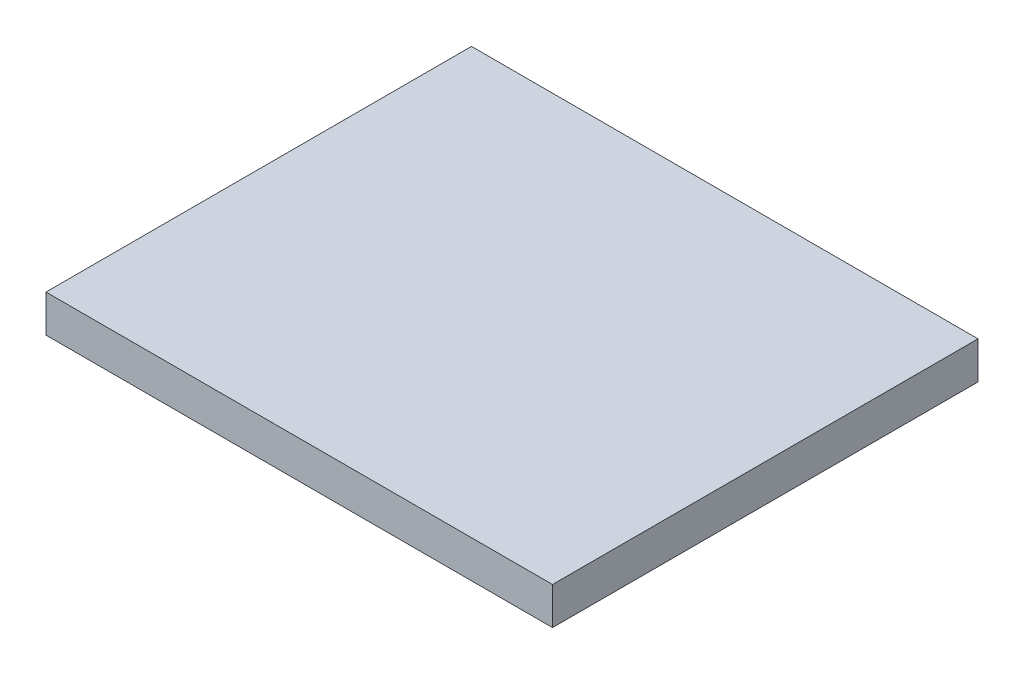
SolidWorks part; units mm, degrees
ref_plane "Front" through (0, 0, 0) normal (0, 0, 1) x (1, 0, 0)
ref_plane "Top" through (0, 0, 0) normal (0, 1, 0) x (1, 0, 0)
ref_plane "Right" through (0, 0, 0) normal (1, 0, 0) x (0, 0, -1)
sketch "Sketch1" plane through (0, 0, 0) normal (0, 1, 0) x (1, 0, 0)
  line L1 (-62.5, -52.5) -> (62.5, -52.5)
  line L2 (-62.5, -52.5) -> (-62.5, 52.5)
  line L3 (-62.5, 52.5) -> (62.5, 52.5)
  line L4 (62.5, -52.5) -> (62.5, 52.5)
  line L5 (-62.5, -52.5) -> (62.5, 52.5) construction
  line L6 (-62.5, 52.5) -> (62.5, -52.5) construction
  point P0 (0, 0)
  dimension "D1" = 125
  dimension "D2" = 105
extrude "Test_Base_Postion" add sketch "Sketch1" along normal blind 9.215
sketch "Thumb_Position" plane through (0, 9.215, 0) normal (0, 1, 0) x (1, 0, 0)
  line L0 (62.5, -52.5) -> (62.5, 52.5) construction
  line L1 (49, -12) -> (17, -12)
  line L2 (49, -12) -> (49, 43)
  line L3 (49, 43) -> (17, 43)
  line L4 (17, -12) -> (17, 43)
  line L5 (33, 43) -> (33, -12) construction
  line L6 (51, -12) -> (15, -12)
  line L7 (51, -12) -> (51, 12)
  line L8 (51, 12) -> (15, 12)
  line L9 (15, -12) -> (15, 12)
  line L10 (33, 12) -> (33, -12) construction
  line L12 (51, 0) -> (15, 0) construction
  circle A1 centre (42, 0) radius 9
  circle A2 centre (42, 0) radius 17.75 construction
  dimension "D6" = 18
  dimension "D7" = 20.5
  dimension "D5" = 35.5
  dimension "D1" = 55
  dimension "D2" = 32
  dimension "D3" = 36
  dimension "D4" = 24
sketch "Finger_Gears_Position" plane through (0, 0, 0) normal (0, -1, 0) x (1, 0, 0)
  line L0 (-30, 32) -> (-30, 49.5) construction
  line L1 (-30, 32) -> (-47.5, 32) construction
  line L2 (-30, -32) -> (-30, -49.5) construction
  line L3 (-30, -32) -> (-47.5, -32) construction
  line L4 (-62.5, -52.5) -> (-62.5, 52.5) construction
  line L5 (-62.5, 52.5) -> (62.5, 52.5) construction
  line L8 (62.5, -52.5) -> (-62.5, -52.5) construction
  line L9 (-62.5, 0) -> (62.5, 0) construction
  line L10 (62.5, 52.5) -> (62.5, -52.5) construction
  line L13 (-30, -32) -> (-43, -32) construction
  line L15 (-43, -48) -> (12, -48) construction
  line L16 (-43, -48) -> (-43, -16) construction
  line L17 (-43, -16) -> (12, -16) construction
  line L18 (12, -48) -> (12, -16) construction
  line L20 (-30, 32) -> (-43, 32) construction
  line L21 (12, -32) -> (-23, -32) construction
  line L22 (-43, 16) -> (12, 16) construction
  line L23 (-43, 16) -> (-43, 48) construction
  line L24 (-43, 48) -> (12, 48) construction
  line L25 (12, 16) -> (12, 48) construction
  line L26 (12, 32) -> (-23, 32) construction
  line L27 (-23, -32) -> (-23, 32) construction
  circle A0 centre (-30, 32) radius 17.5 construction
  circle A1 centre (-30, -32) radius 17.5 construction
  dimension "D1" = 35
  dimension "D2" = 15
  dimension "D3" = 3
  dimension "D4" = 3
  dimension "D5" = 13
  dimension "D6" = 55
  dimension "D7" = 32
  dimension "D8" = 13
  dimension "D9" = 55
  dimension "D10" = 32
  dimension "D11" = 35
  dimension "D12" = 35
sketch "Fingers_Position" plane through (0, 9.215, 0) normal (0, 1, 0) x (1, 0, 0)
  line L0 (12, 32) -> (-23, 32) construction
  line L1 (12, 16) -> (-43, 16)
  line L2 (12, 16) -> (12, 48)
  line L3 (12, 48) -> (-43, 48)
  line L4 (-43, 16) -> (-43, 48)
  line L5 (12, -48) -> (-43, -48)
  line L6 (12, -48) -> (12, -16)
  line L7 (12, -16) -> (-43, -16)
  line L8 (-43, -48) -> (-43, -16)
  line L9 (-23, 32) -> (-23, -32) construction
  line L10 (-23, -32) -> (12, -32) construction
sketch "Thumb_Knuckle_Mount_Position" plane through (0, 0, 0) normal (0, -1, 0) x (1, 0, 0)
  circle A0 centre (42, 0) radius 17.75
  dimension "D1" = 35.5
sketch "Gears_Position" plane through (0, 0, 0) normal (0, -1, 0) x (1, 0, 0)
  line L0 (-35.4839, 5.8991) -> (-18.0493, 1.4232) construction
  line L1 (-38.4678, -5.724) -> (-3.5985, -14.6757) construction
  line L2 (-38.4678, -5.724) -> (-32.5, 17.5222) construction
  line L3 (-32.5, 17.5222) -> (2.3693, 8.5705) construction
  line L4 (-3.5985, -14.6757) -> (2.3693, 8.5705) construction
  line L5 (-38.4678, -5.724) -> (2.3693, 8.5705) construction
  line L6 (-32.5, 17.5222) -> (-3.5985, -14.6757) construction
  line L12 (-62.5, -52.5) -> (-62.5, 52.5) construction
  circle A0 centre (-30, -32) radius 16.25
  circle A1 centre (-47.5, -9.4768) radius 12.2727
  circle A2 centre (-26.7666, 3.6611) radius 12.2727
  circle A3 centre (-30, 32) radius 16.25
  circle A4 centre (-26.7666, 3.6611) radius 9 construction
  circle A5 centre (-30, 32) radius 17.5 construction
  point P14 (-18.0493, 1.4232)
  dimension "D1" = 32.5
  dimension "D2" = 24.5455
  dimension "D3" = 36
  dimension "D4" = 24
  dimension "D5" = 30
  dimension "D6" = 15
sketch "XL320_Position" plane through (0, 9.215, 0) normal (0, 1, 0) x (1, 0, 0)
  line L8 (-35.4839, -5.8991) -> (-18.0493, -1.4232) construction
  line L9 (-32.5, -17.5222) -> (2.3693, -8.5705)
  line L10 (-32.5, -17.5222) -> (-38.4678, 5.724)
  line L13 (-38.4678, 5.724) -> (-3.5985, 14.6757)
  line L16 (2.3693, -8.5705) -> (-3.5985, 14.6757)
  line L19 (-32.5, -17.5222) -> (-3.5985, 14.6757) construction
  line L20 (-38.4678, 5.724) -> (2.3693, -8.5705) construction
  circle A3 centre (-26.7666, -3.6611) radius 9
  point P3 (-18.0493, -1.4232)
  dimension "D1" = 18
equation "\"D1@Gears_Position\"=26*(35/(26+2))"
equation "\"D2@Gears_Position\"=20*(27/(20+2))"
